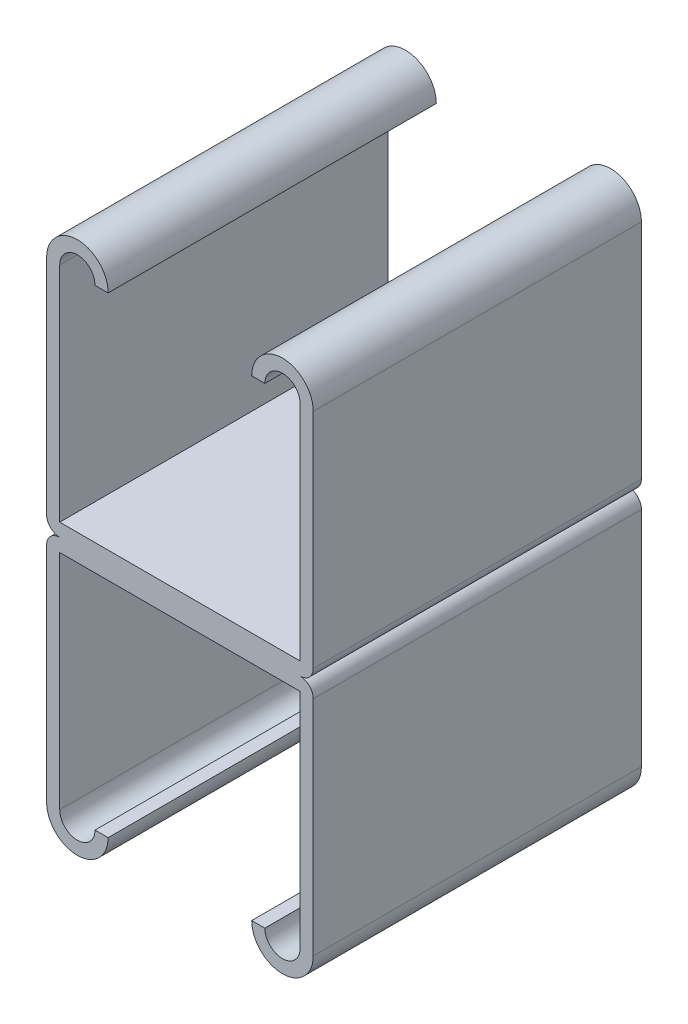
SolidWorks part; units mm, degrees
ref_plane "Plane1" through (0, 0, 0) normal (0, 0, 1) x (1, 0, 0)
ref_plane "Plane2" through (0, 0, 0) normal (0, 1, 0) x (1, 0, 0)
ref_plane "Plane3" through (0, 0, 0) normal (1, 0, 0) x (0, 0, -1)
sketch "Sketch1" plane through (0, 0, 0) normal (0, 0, 1) x (1, 0, 0)
  line L0 (-10.3188, 18.2563) -> (-10.3187, 1.016)
  line L1 (-9.3028, 0) -> (9.3027, 0)
  line L2 (10.3187, 1.016) -> (10.3187, 18.2562)
  line L3 (-6.5723, 18.2563) -> (-5.5563, 18.2563)
  line L4 (5.5562, 18.2562) -> (6.5722, 18.2562)
  line L6 (-9.3028, 18.2563) -> (-9.3027, 1.016)
  line L7 (-9.3027, 1.016) -> (9.3027, 1.016)
  line L8 (9.3027, 1.016) -> (9.3027, 18.2562)
  line L10 (-25.4, 20.6375) -> (25.4, 20.6375) construction
  arc A0 (10.3187, 18.2562) -> (5.5562, 18.2562) centre (7.9375, 18.2562) ccw
  arc A1 (-10.3188, 18.2563) -> (-5.5563, 18.2563) centre (-7.9375, 18.2563) cw
  arc A2 (-9.3028, 0) -> (-10.3187, 1.016) centre (-9.3028, 1.016) cw
  arc A3 (9.3027, 0) -> (10.3187, 1.016) centre (9.3027, 1.016) ccw
  arc A4 (-9.3028, 18.2563) -> (-6.5723, 18.2563) centre (-7.9375, 18.2563) cw
  arc A5 (9.3027, 18.2562) -> (6.5722, 18.2562) centre (7.9375, 18.2562) ccw
  dimension "D1" = 1.016
  dimension "D3" = 10.3187
  dimension "Width" = 20.6375
  dimension "D8" = 20.6375
  dimension "D2" = 4.7625
  dimension "D4" = 1.016
  dimension "D5" = 11.1125
  dimension "D6" = 4.7625
  dimension "gauge" = 1.016
extrude "Base-Extrude" add sketch "Sketch1" along normal mid plane 25.4
mirror "Mirror1" about plane through (0, 0, 0) normal (0, 1, 0) of "Base-Extrude"
equation "\"D3@Sketch1\" = \"Width@Sketch1\" / 2"
equation "\"D1@Sketch1\" = \"gauge@Sketch1\""
